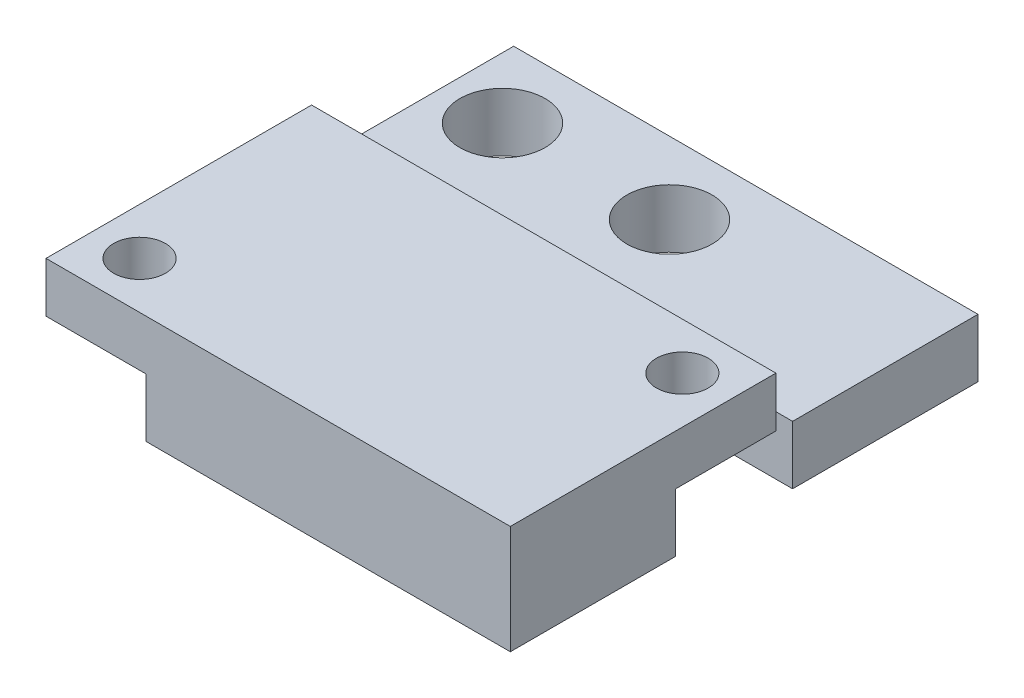
SolidWorks part; units mm, degrees
ref_plane "Front Plane" through (0, 0, 0) normal (0, 0, 1) x (1, 0, 0)
ref_plane "Top Plane" through (0, 0, 0) normal (0, 1, 0) x (1, 0, 0)
ref_plane "Right Plane" through (0, 0, 0) normal (1, 0, 0) x (0, 0, -1)
sketch "Sketch1" plane through (0, 0, 0) normal (0, 1, 0) x (1, 0, 0)
  line L0 (13.65, 23.68) -> (3.65, 23.68) construction
  line L1 (0, 0) -> (27.8, 0)
  line L2 (0, 0) -> (0, 28)
  line L3 (0, 28) -> (27.8, 28)
  line L4 (27.8, 0) -> (27.8, 28)
  circle A0 centre (13.65, 23.68) radius 2.55
  circle A1 centre (3.65, 23.68) radius 2.55
  dimension "D2" = 5.1
  dimension "D1" = 10
  dimension "D3" = 27.8
  dimension "D4" = 28
  dimension "D5" = 23.68
  dimension "D6" = 13.65
extrude "Boss-Extrude1" add sketch "Sketch1" along normal blind 3.5
sketch "Sketch2" plane through (0, 3.5, 0) normal (0, 1, 0) x (1, 0, 0)
  line L0 (27.8, 0) -> (27.8, 28) construction
  line L1 (0, 0) -> (27.8, 0)
  line L2 (0, 0) -> (0, 15.9)
  line L3 (0, 15.9) -> (27.8, 15.9)
  line L4 (27.8, 0) -> (27.8, 15.9)
  circle A0 centre (2.8, 2.8) radius 1.55
  circle A1 centre (25, 13.1) radius 1.55
  dimension "D2" = 3.1
  dimension "D1" = 15.9
  dimension "D3" = 2.8
  dimension "D4" = 2.8
  dimension "D5" = 2.8
  dimension "D6" = 2.8
extrude "Boss-Extrude2" add sketch "Sketch2" along normal blind 3
sketch "Sketch3" plane through (0, 0, 0) normal (0, -1, 0) x (1, 0, 0)
  line L0 (27.8, -28) -> (0, -28)
  line L1 (27.8, -28) -> (0, -28)
  line L2 (0, -28) -> (0, -15.9)
  line L3 (0, -28) -> (0, -15.9)
  line L4 (0, -15.9) -> (0, 0)
  line L6 (0, 0) -> (27.8, 0)
  line L8 (27.8, 0) -> (27.8, -15.9)
  line L10 (27.8, -15.9) -> (27.8, -28)
  line L11 (27.8, -15.9) -> (27.8, -28)
  line L12 (27.8, -28) -> (0, -28)
  line L13 (27.8, -28) -> (0, -28)
  line L14 (0, -28) -> (0, -15.9)
  line L15 (0, -28) -> (0, -15.9)
  line L16 (0, -15.9) -> (0, 0)
  line L17 (0, -15.9) -> (0, 0)
  line L18 (0, 0) -> (27.8, 0)
  line L20 (27.8, 0) -> (27.8, -15.9)
  line L21 (27.8, 0) -> (27.8, -15.9)
  line L22 (27.8, -15.9) -> (27.8, -28)
  line L23 (27.8, -15.9) -> (27.8, -28)
  line L25 (0, 0) -> (6, 0)
  line L26 (0, 0) -> (0, -6)
  line L27 (0, -6) -> (6, -6)
  line L28 (0, 0) -> (0, -15.9)
  line L29 (27.8, 0) -> (0, 0)
  line L30 (27.8, -15.9) -> (27.8, 0)
  line L31 (0, -15.9) -> (27.8, -15.9)
  line L32 (0, 0) -> (0, -15.9)
  line L34 (27.8, -15.9) -> (27.8, 0)
  line L36 (6, 0) -> (6, -6)
  line L37 (27.8, -15.9) -> (22.8, -15.9)
  line L38 (27.8, -15.9) -> (27.8, -10.9)
  line L39 (27.8, -10.9) -> (22.8, -10.9)
  line L40 (22.8, -15.9) -> (22.8, -10.9)
  line M16 (0, 0) -> (0, -28)
  line M19 (27.8, 0) -> (0, 0)
  dimension "D2" = 6
  dimension "D3" = 6
  dimension "D4" = 5
  dimension "D5" = 5
  dimension "D1" = 0
extrude "Cut-Extrude5" cut sketch "Sketch3" against normal blind 3.5 contours L36 L27 M19 M16
sketch "Sketch4" plane through (0, 0, 0) normal (0, -1, 0) x (1, 0, 0)
  line L5 (27.8, 0) -> (27.8, -28) construction
  line L6 (27.8, -16.9) -> (21.8, -16.9)
  line L7 (27.8, -16.9) -> (27.8, -9.9)
  line L8 (27.8, -9.9) -> (21.8, -9.9)
  line L9 (0, 0) -> (0, -15.9)
  line L10 (27.8, 0) -> (0, 0)
  line L11 (27.8, -15.9) -> (27.8, 0)
  line L12 (0, -15.9) -> (27.8, -15.9)
  line L13 (0, 0) -> (0, -15.9)
  line L14 (27.8, 0) -> (0, 0)
  line L15 (27.8, -15.9) -> (27.8, 0)
  line L16 (0, -15.9) -> (27.8, -15.9)
  line L17 (21.8, -16.9) -> (21.8, -9.9)
  line M16 (27.8, -28) -> (27.8, 0)
  dimension "D2" = 6
  dimension "D3" = 7
  dimension "D4" = 1
  dimension "D1" = 0
extrude "Cut-Extrude7" cut sketch "Sketch4" against normal blind 3.5 contours L17 L16 L7 L8 | L17 L6 L16 M16
sketch "Sketch5" plane through (0, 0, 0) normal (0, -1, 0) x (1, 0, 0)
  line L1 (13.65, -13.68) -> (13.65, -23.68) construction
  circle A0 centre (13.65, -23.68) radius 2.55 construction
  circle A1 centre (13.65, -23.68) radius 2.55
  circle A2 centre (13.65, -13.68) radius 5
  dimension "D1" = 10
  dimension "D2" = 10
extrude "Cut-Extrude8" cut sketch "Sketch5" against normal blind 3
